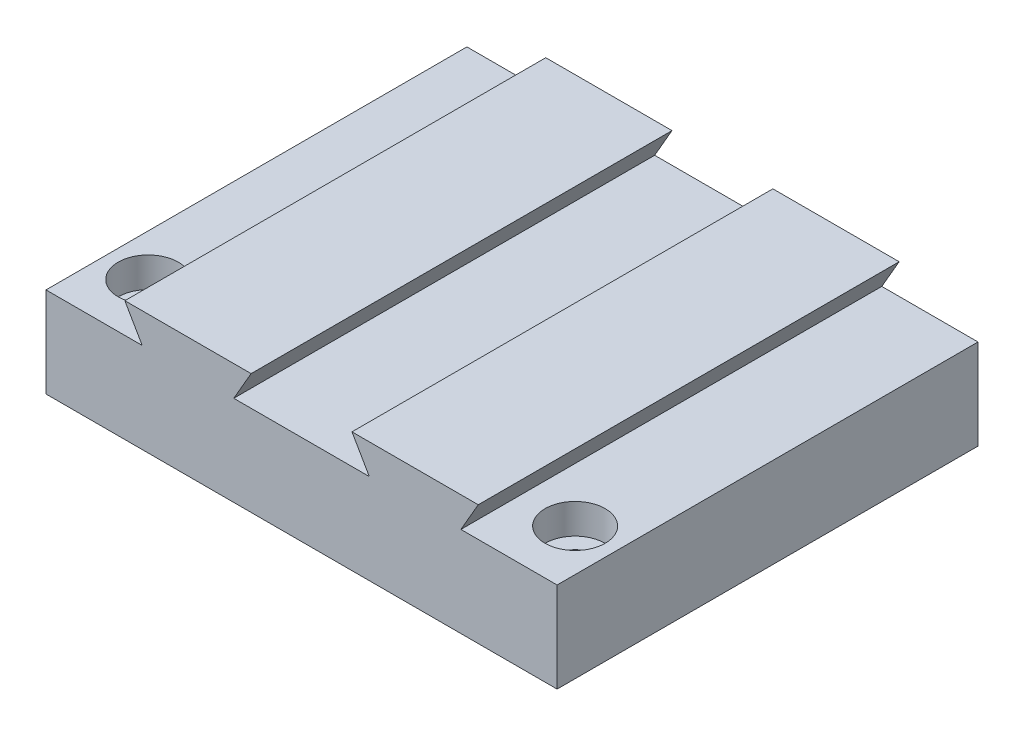
SolidWorks part; units mm, degrees
ref_plane "Alzado" through (0, 0, 0) normal (0, 0, 1) x (1, 0, 0)
ref_plane "Planta" through (0, 0, 0) normal (0, 1, 0) x (1, 0, 0)
ref_plane "Vista lateral" through (0, 0, 0) normal (1, 0, 0) x (0, 0, -1)
sketch "Croquis1" plane through (0, 0, 0) normal (0, 1, 0) x (1, 0, 0)
  line L1 (-42.5, -35) -> (42.5, -35)
  line L2 (-42.5, -35) -> (-42.5, 35)
  line L3 (-42.5, 35) -> (42.5, 35)
  line L4 (42.5, -35) -> (42.5, 35)
  line L5 (-42.5, -35) -> (42.5, 35) construction
  line L6 (-42.5, 35) -> (42.5, -35) construction
  point P0 (0, 0)
extrude "Saliente-Extruir1" add sketch "Croquis1" along normal blind 15
sketch "Croquis3" plane through (0, 0, 0) normal (0, -1, 0) x (1, 0, 0)
  line L0 (-42.5, 0) -> (-30.5, 0) construction
  line L1 (-42.5, -35) -> (-42.5, 35) construction
  line L2 (42.5, 0) -> (30.5, 0) construction
  line L3 (42.5, 35) -> (42.5, -35) construction
  circle A0 centre (-30.5, 0) radius 4.15
  circle A1 centre (30.5, 0) radius 4.15
extrude "Cortar-Extruir1" cut sketch "Croquis3" against normal blind 10
sketch "Croquis4" plane through (0, 0, 0) normal (0, -1, 0) x (-1, 0, 0)
  line L0 (-26.35, 0) -> (26.35, 0) construction
  circle A0 centre (-30.5, 0) radius 4.15 construction
  circle A1 centre (30.5, 0) radius 4.15 construction
  text T0 "11" font "Century Gothic" height 6
extrude "Cortar-Extruir2" cut sketch "Croquis4" against normal blind 1
sketch "Croquis5" plane through (0, 0, 0) normal (0, -1, 0) x (1, 0, 0)
  line L0 (30.5, -4.15) -> (30.5, -10)
  line L1 (30.5, 4.15) -> (30.5, 10)
  line L2 (-30.5, -10) -> (-30.5, -4.15)
  line L3 (-30.5, 4.15) -> (-30.5, 10)
  arc A0 (30.5, 10) -> (30.5, -10) centre (30.5, 0) ccw
  arc A1 (-30.5, -10) -> (-30.5, 10) centre (-30.5, 0) ccw
  arc A2 (30.5, 4.15) -> (30.5, -4.15) centre (30.5, 0) ccw
  arc A3 (-30.5, -4.15) -> (-30.5, 4.15) centre (-30.5, 0) ccw
  dimension "D1" = 20
  dimension "D2" = 20
extrude "Saliente-Extruir4" add sketch "Croquis5" along normal blind 10
sketch "Croquis8" plane through (30.5, 0, 0) normal (1, 0, 0) x (0, 0, -1)
  line L1 (-10, -10) -> (-10, 0) construction
  line L2 (10, -10) -> (10, 0) construction
  circle A0 centre (7.075, -4.6098) radius 1.75
  circle A1 centre (-7.07, -4.6098) radius 1.75
  dimension "D1" = 3.5
  dimension "D2" = 2.925
  dimension "D3" = 3.5
  dimension "D4" = 2.93
sketch "Croquis9" plane through (30.5, 0, 0) normal (1, 0, 0) x (0, 0, -1)
  line L1 (4.15, 0) -> (10, 0)
  line L2 (4.15, 0) -> (4.15, -10)
  line L3 (4.15, -10) -> (10, -10)
  line L4 (10, 0) -> (10, -10)
  line L5 (-10, 0) -> (-4.15, 0)
  line L6 (-10, 0) -> (-10, -10)
  line L7 (-10, -10) -> (-4.15, -10)
  line L8 (-4.15, 0) -> (-4.15, -10)
extrude "Saliente-Extruir5" add sketch "Croquis9" against normal blind 9
sketch "Croquis10" plane through (21.5, 0, 0) normal (-1, 0, 0) x (0, 0, 1)
  line L1 (10, 0) -> (-10, 0)
  line L2 (10, 0) -> (10, -10)
  line L3 (10, -10) -> (-10, -10)
  line L4 (-10, 0) -> (-10, -10)
extrude "Saliente-Extruir6" add sketch "Croquis10" along normal blind 1
extrude "Cortar-Extruir4" cut sketch "Croquis8" against normal up to next contours A1 | A0
sketch "Croquis12" plane through (-30.5, 0, 0) normal (-1, 0, 0) x (0, 0, 1)
  line L0 (10, -10) -> (10, 0) construction
  line L1 (-10, -10) -> (-10, 0) construction
  line L2 (-4.15, 0) -> (-10, 0) construction
  line L3 (10, 0) -> (4.15, 0) construction
  line L5 (10, -10) -> (4.15, -10)
  line L6 (10, -10) -> (10, 0)
  line L7 (10, 0) -> (4.15, 0)
  line L8 (4.15, -10) -> (4.15, 0)
  line L9 (-4.15, -10) -> (-10, -10)
  line L10 (-4.15, -10) -> (-4.15, 0)
  line L11 (-4.15, 0) -> (-10, 0)
  line L12 (-10, -10) -> (-10, 0)
  circle A0 centre (7.07, -5) radius 1.75
  circle A1 centre (-7.07, -5) radius 1.75
  dimension "D1" = 3.5
  dimension "D2" = 3.5
  dimension "D4" = 2.93
  dimension "D5" = 5
  dimension "D6" = 5
  dimension "D3" = 2.93
extrude "Saliente-Extruir7" add sketch "Croquis12" against normal blind 9
sketch "Croquis13" plane through (-21.5, 0, 0) normal (1, 0, 0) x (0, 0, -1)
  line L1 (10, 0) -> (-10, 0)
  line L2 (10, 0) -> (10, -10)
  line L3 (10, -10) -> (-10, -10)
  line L4 (-10, 0) -> (-10, -10)
extrude "Saliente-Extruir8" add sketch "Croquis13" along normal blind 1
sketch "Croquis14" plane through (-30.5, 0, 0) normal (-1, 0, 0) x (0, 0, 1)
  line L0 (10, -10) -> (10, 0) construction
  line L1 (-10, -10) -> (-10, 0) construction
  line L2 (10, -10) -> (4.15, -10) construction
  line L3 (-4.15, -10) -> (-10, -10) construction
  circle A0 centre (7.07, -5) radius 1.75
  circle A1 centre (-7.07, -5) radius 1.75
  dimension "D1" = 3.5
  dimension "D2" = 3.5
  dimension "D3" = 2.93
  dimension "D4" = 2.93
  dimension "D5" = 5
  dimension "D6" = 5
extrude "Cortar-Extruir5" cut sketch "Croquis14" against normal blind 11
sketch "Croquis15" plane through (0, 0, -35) normal (0, 0, -1) x (-1, 0, 0)
  line L0 (-26.5, 15) -> (-29.3868, 20)
  line L1 (-42.5, 15) -> (42.5, 15) construction
  line L2 (-29.3868, 20) -> (-8.3868, 20)
  line L3 (-8.3868, 20) -> (-11.2735, 15)
  line L4 (0, 0) -> (0, 23.6995) construction
  line L5 (-42.5, 0) -> (42.5, 0) construction
  line L6 (8.3868, 20) -> (11.2735, 15)
  line L7 (26.5, 15) -> (29.3868, 20)
  line L8 (29.3868, 20) -> (8.3868, 20)
  line L9 (-26.5, 15) -> (-11.2735, 15)
  line L10 (11.2735, 15) -> (26.5, 15)
  dimension "D1" = 21
  dimension "D2" = 60
  dimension "D3" = 60
  dimension "D4" = 5
  dimension "D5" = 16
extrude "Saliente-Extruir10" add sketch "Croquis15" against normal through all
sketch "Croquis22" plane through (0, 15, 0) normal (0, 1, 0) x (1, 0, 0)
  line L0 (42.5, -35) -> (42.5, 35) construction
  line L1 (26.5, -35) -> (42.5, -35) construction
  circle A0 centre (35.5, -25) radius 5
  dimension "D1" = 7
  dimension "D2" = 10
sketch "Croquis23" plane through (0, 15, 0) normal (0, 1, 0) x (1, 0, 0)
  line L0 (-42.5, 35) -> (-42.5, -35) construction
  line L1 (-42.5, -35) -> (-26.5, -35) construction
  circle A0 centre (-35.5, -25) radius 5
  dimension "D1" = 7
  dimension "D2" = 10
extrude "Cortar-Extruir9" cut sketch "Croquis23" against normal blind 5
extrude "Cortar-Extruir10" cut sketch "Croquis22" against normal blind 5 contours A0
sketch "Croquis24" plane through (0, 10, 0) normal (0, 1, 0) x (1, 0, 0)
  circle A0 centre (-35.5, -25) radius 2.25
  circle A1 centre (35.5, -25) radius 2.25
  dimension "D1" = 4.5
  dimension "D2" = 4.5
extrude "Cortar-Extruir11" cut sketch "Croquis24" against normal through all and the other way through all
sketch "Croquis25" plane through (0, 0, 0) normal (0, -1, 0) x (1, 0, 0)
  line L0 (42.5, -35) -> (-42.5, -35) construction
  line L1 (-6.1, -26) -> (5.9, -26)
  line L2 (-6.1, -26) -> (-6.1, -20)
  line L3 (-6.1, -20) -> (5.9, -20)
  line L4 (5.9, -26) -> (5.9, -20)
  line L5 (-6.1, -26) -> (5.9, -20) construction
  line L6 (-6.1, -20) -> (5.9, -26) construction
  line L7 (-42.5, -35) -> (-42.5, 35) construction
  point P0 (-0.1, -23)
  dimension "D1" = 12
  dimension "D2" = 6
  dimension "D3" = 9
  dimension "D4" = 36.4
extrude "Saliente-Extruir11" add sketch "Croquis25" along normal blind 28
fillet "Redondeo1" radius 4 4 edges at (-0.1, 0, -20) (5.9, 0, -23) (-0.1, 0, -26) (-6.1, 0, -23)
sketch "Croquis26" plane through (0, 0, -35) normal (0, 0, -1) x (-1, 0, 0)
  line L0 (26.5, 15) -> (42.5, 15) construction
  line L1 (29.3868, 20) -> (8.3868, 20) construction
  dimension "D1" = 5
